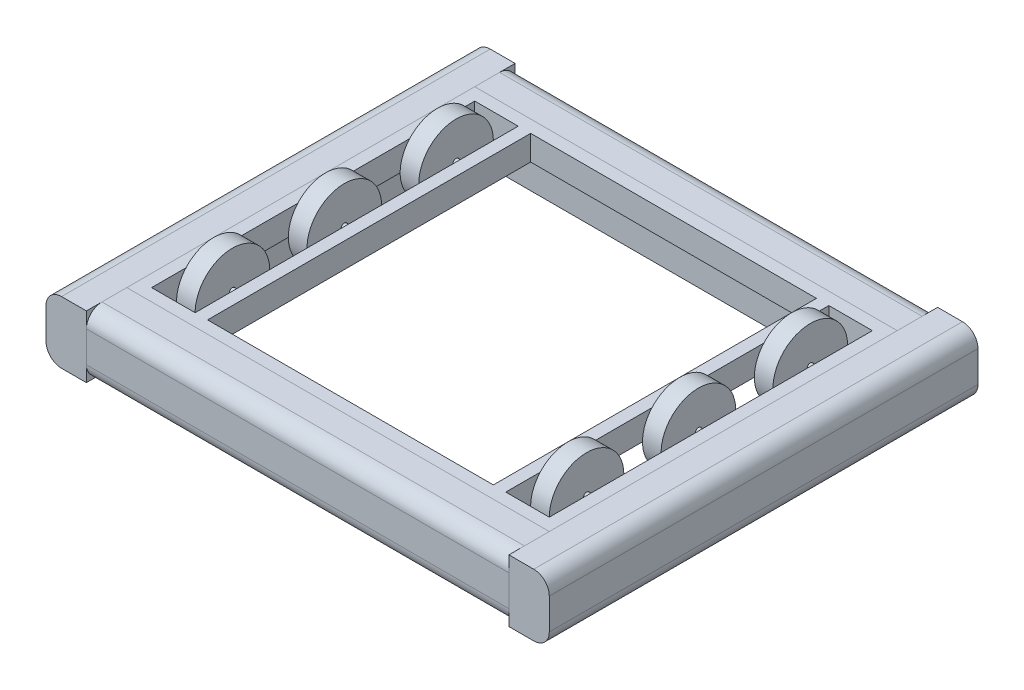
SolidWorks part; units mm, degrees
ref_plane "Front Plane" through (0, 0, 0) normal (0, 0, 1) x (1, 0, 0)
ref_plane "Top Plane" through (0, 0, 0) normal (0, 1, 0) x (1, 0, 0)
ref_plane "Right Plane" through (0, 0, 0) normal (1, 0, 0) x (0, 0, -1)
sketch "Sketch1" plane through (0, 0, 0) normal (0, 1, 0) x (1, 0, 0)
  line L0 (25.4, 25.4) -> (25.4, 685.8)
  line L1 (0, 0) -> (863.6, 0)
  line L2 (0, 0) -> (0, 711.2)
  line L3 (0, 711.2) -> (863.6, 711.2)
  line L4 (863.6, 0) -> (863.6, 711.2)
  line L5 (25.4, 685.8) -> (838.2, 685.8)
  line L6 (838.2, 25.4) -> (838.2, 685.8)
  line L7 (25.4, 25.4) -> (838.2, 25.4)
  line L8 (114.3, 685.8) -> (114.3, 25.4)
  line L9 (139.7, 685.8) -> (139.7, 25.4)
  line L10 (431.8, 685.8) -> (431.8, 25.4) construction
  line L11 (749.3, 685.8) -> (749.3, 25.4)
  line L12 (723.9, 685.8) -> (723.9, 25.4)
  dimension "D1" = 711.2
  dimension "D2" = 863.6
  dimension "D4" = 25.4
  dimension "D5" = 88.9
  dimension "D3" = 25.4
extrude "Boss-Extrude1" add sketch "Sketch1" along normal blind 50.8 contours L1 L4 L3 L2 L7 L0 L5 L6 | L9 L5 L8 L7 | L5 L12 L7 L11
ref_plane "Plane1" through (793.75, 0, 0) normal (1, 0, 0) x (0, 0, -1)
sketch "Sketch3" plane through (793.75, 0, 0) normal (1, 0, 0) x (0, 0, -1)
  line L2 (355.6, 0) -> (355.6, 50.8) construction
  line L6 (0, 0) -> (711.2, 0)
  line L7 (711.2, 0) -> (711.2, 50.8)
  line L8 (711.2, 50.8) -> (0, 50.8)
  line L9 (0, 50.8) -> (0, 0)
  line L10 (0, 0) -> (711.2, 0) construction
  line L11 (711.2, 0) -> (711.2, 50.8) construction
  line L12 (711.2, 50.8) -> (0, 50.8) construction
  line L13 (0, 50.8) -> (0, 0) construction
  circle A0 centre (127, 25.4) radius 76.2
  circle A1 centre (355.6, 25.4) radius 76.2
  circle A2 centre (584.2, 25.4) radius 76.2
  dimension "D1" = 152.4
  dimension "D3" = 228.6
  dimension "D2" = 0
extrude "Boss-Extrude2" add sketch "Sketch3" along normal blind 19.05 and the other way blind 19.05 separate body
sketch "Sketch4" plane through (793.75, 0, 0) normal (1, 0, 0) x (0, 0, -1)
  circle A0 centre (584.2, 25.4) radius 6.35
  circle A1 centre (355.6, 25.4) radius 6.35
  circle A2 centre (127, 25.4) radius 6.35
  dimension "D1" = 12.7
extrude "Boss-Extrude3" add sketch "Sketch4" along normal up to surface and the other way up to surface up to face at (838.2, 25.4, -355.6) other way up to face at (749.3, 25.4, -355.6)
ref_plane "Plane3" through (69.85, 0, 0) normal (1, 0, 0) x (0, 0, -1)
sketch "Sketch5" plane through (69.85, 0, 0) normal (1, 0, 0) x (0, 0, -1)
  circle A0 centre (584.2, 25.4) radius 76.2 construction
  circle A1 centre (355.6, 25.4) radius 76.2 construction
  circle A2 centre (127, 25.4) radius 76.2 construction
  circle A3 centre (584.2, 25.4) radius 76.2
  circle A4 centre (355.6, 25.4) radius 76.2
  circle A5 centre (127, 25.4) radius 76.2
extrude "Boss-Extrude4" add sketch "Sketch5" along normal blind 19.05 and the other way blind 19.05 separate body
sketch "Sketch6" plane through (69.85, 0, 0) normal (1, 0, 0) x (0, 0, -1)
  circle A0 centre (127, 25.4) radius 6.35
  circle A1 centre (355.6, 25.4) radius 6.35
  circle A2 centre (584.2, 25.4) radius 6.35
  dimension "D1" = 12.7
extrude "Boss-Extrude5" add sketch "Sketch6" along normal up to surface and the other way up to surface up to face at (114.3, 25.4, -355.6) other way up to face at (25.4, 25.4, -355.6)
sketch "Sketch7" plane through (0, 0, -711.2) normal (0, 0, -1) x (-1, 0, 0)
  line L0 (-882.65, -76.2) -> (-914.4, -76.2)
  line L1 (-863.6, 50.8) -> (-882.65, 50.8)
  line L2 (-863.6, 50.8) -> (-863.6, -76.2)
  line L3 (-863.6, -76.2) -> (-882.65, -76.2)
  line L4 (-882.65, 50.8) -> (-882.65, -76.2)
  line L5 (-774.7, 101.6) -> (-812.8, 101.6) construction
  line L6 (-882.65, 50.8) -> (-914.4, 50.8)
  line L7 (-946.15, -44.45) -> (-946.15, 19.05)
  line L8 (-431.8, 50.8) -> (-431.8, 0) construction
  line L9 (0, 50.8) -> (-863.6, 50.8) construction
  line L10 (0, 0) -> (-863.6, 0) construction
  line L11 (82.55, -44.45) -> (82.55, 19.05)
  line L12 (19.05, 50.8) -> (50.8, 50.8)
  line L13 (19.05, 50.8) -> (19.05, -76.2)
  line L14 (0, -76.2) -> (19.05, -76.2)
  line L15 (0, 50.8) -> (0, -76.2)
  line L16 (0, 50.8) -> (19.05, 50.8)
  line L17 (19.05, -76.2) -> (50.8, -76.2)
  circle A0 centre (-914.4, -44.45) radius 31.75
  circle A1 centre (-914.4, 19.05) radius 31.75
  circle A2 centre (50.8, 19.05) radius 31.75
  circle A3 centre (50.8, -44.45) radius 31.75
  line M8 (0, 0) -> (0, 50.8)
  line M10 (-863.6, 50.8) -> (-863.6, 0)
  dimension "D4" = 63.5
  dimension "D1" = 127
  dimension "D2" = 19.05
  dimension "D3" = 50.8
extrude "Boss-Extrude6" add sketch "Sketch7" along normal blind 82.55 and the other way blind 793.75 separate body contours L1 L4 L3 L2 M10 | A0 L0 L4 | A0 | A1 A0 L4 | A1 L4 L6 | A1 | A1 L7 A0 | A2 | A2 A3 L11 | A3 | L16 L15 L14 L13 M8 | L13 A3 A2 | L13 A2 L12 | L17 A3 L13
sketch "Sketch8" plane through (863.6, 0, 0) normal (-1, 0, 0) x (0, 0, 1)
  line L0 (82.55, -76.2) -> (-793.75, -76.2) construction
  line L1 (-711.2, 50.8) -> (-730.25, 50.8)
  line L2 (-711.2, 50.8) -> (-711.2, -76.2)
  line L3 (-711.2, -76.2) -> (-730.25, -76.2)
  line L4 (-730.25, 50.8) -> (-730.25, -76.2)
  line L5 (-730.25, -76.2) -> (-762, -76.2)
  line L6 (-793.75, -44.45) -> (-793.75, 19.05)
  line L7 (-762, 50.8) -> (-730.25, 50.8)
  line L8 (-355.6, 50.8) -> (-355.6, 0) construction
  line L9 (0, 50.8) -> (-711.2, 50.8) construction
  line L10 (0, 0) -> (-711.2, 0) construction
  line L11 (50.8, 50.8) -> (19.05, 50.8)
  line L12 (82.55, -44.45) -> (82.55, 19.05)
  line L13 (19.05, -76.2) -> (50.8, -76.2)
  line L14 (19.05, 50.8) -> (19.05, -76.2)
  line L15 (0, -76.2) -> (19.05, -76.2)
  line L16 (0, 50.8) -> (0, -76.2)
  line L17 (0, 50.8) -> (19.05, 50.8)
  circle A0 centre (-762, -44.45) radius 31.75
  circle A1 centre (-762, 19.05) radius 31.75
  circle A2 centre (50.8, 19.05) radius 31.75
  circle A3 centre (50.8, -44.45) radius 31.75
  line M8 (82.55, 50.8) -> (-793.75, 50.8)
  line M9 (-793.75, 50.8) -> (-793.75, -76.2)
  line M10 (-793.75, -76.2) -> (82.55, -76.2)
  line M11 (82.55, -76.2) -> (82.55, 50.8)
  dimension "D2" = 63.5
  dimension "D1" = 19.05
extrude "Boss-Extrude7" add sketch "Sketch8" along normal up to surface (863.6 mm away) separate body contours A3 | L16 L14 M8 M10 | A3 L14 M10 | L14 A3 A2 | L14 A2 M8 | A2 A3 M11 | A2 | L4 L2 M8 M10 | A0 L4 M10 | A0 | A1 A0 L4 | A1 | A1 A0 M9 | A1 L4 M8 up to face at (0, 25.4, -355.6)
